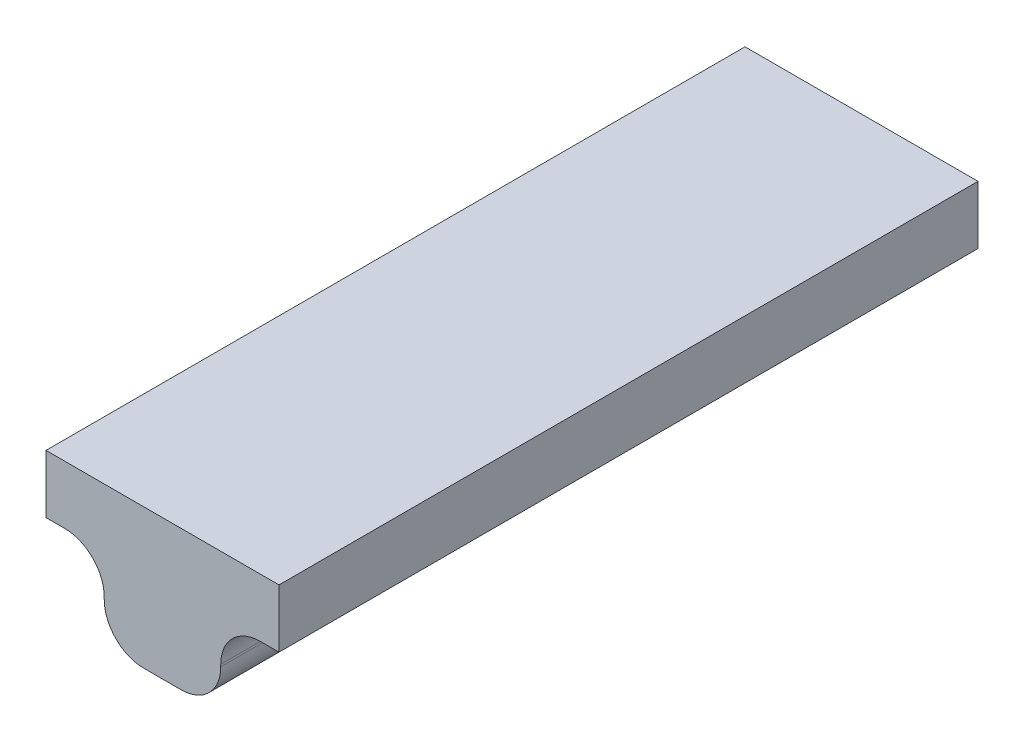
SolidWorks part; units mm, degrees
ref_plane "前视基准面" through (0, 0, 0) normal (0, 0, 1) x (1, 0, 0)
ref_plane "上视基准面" through (0, 0, 0) normal (0, 1, 0) x (1, 0, 0)
ref_plane "右视基准面" through (0, 0, 0) normal (1, 0, 0) x (0, 0, -1)
sketch "草图1" plane through (0, 0, 0) normal (0, 0, 1) x (1, 0, 0)
  line L0 (-0.5, -0.5) -> (0.5, -0.5) construction
  line L1 (-1, 0) -> (1, 0)
  line L2 (-1, 0) -> (-1, -0.5)
  line L3 (-1, -0.5) -> (-0.84, -0.5)
  line L4 (1, 0) -> (1, -0.5)
  line L5 (-1, 0) -> (1, -0.5) construction
  line L6 (-1, -0.5) -> (1, 0) construction
  line L7 (-0.5, -0.5) -> (0.5, -0.5) construction
  line L8 (-0.5, -0.84) -> (-0.5, -0.86)
  line L9 (-0.16, -1.2) -> (0.16, -1.2)
  line L10 (0.5, -0.84) -> (0.5, -0.86)
  line L11 (-0.5, -0.5) -> (0.5, -1.2) construction
  line L12 (-0.5, -1.2) -> (0.5, -0.5) construction
  line L13 (0.84, -0.5) -> (1, -0.5)
  arc A0 (0.16, -1.2) -> (0.5, -0.86) centre (0.16, -0.86) ccw
  arc A1 (-0.5, -0.86) -> (-0.16, -1.2) centre (-0.16, -0.86) ccw
  arc A2 (0.84, -0.5) -> (0.5, -0.84) centre (0.84, -0.84) ccw
  arc A3 (-0.84, -0.5) -> (-0.5, -0.84) centre (-0.84, -0.84) cw
  point P4 (0, -0.25)
  point P11 (0, -0.85)
  dimension "D5" = 0.34
  dimension "D1" = 0.5
  dimension "D2" = 2
  dimension "D3" = 1
  dimension "D4" = 1.2
extrude "凸台-拉伸1" add sketch "草图1" along normal blind 6
ref_plane "基准面1" through (0, 0, 3) normal (0, 0, 1) x (1, 0, 0)
sketch "草图2" plane through (0, 0, 3) normal (0, 0, 1) x (1, 0, 0)
  line L0 (1, 0) -> (-1, 0) construction
  line L1 (1, 0) -> (-1, 0)
